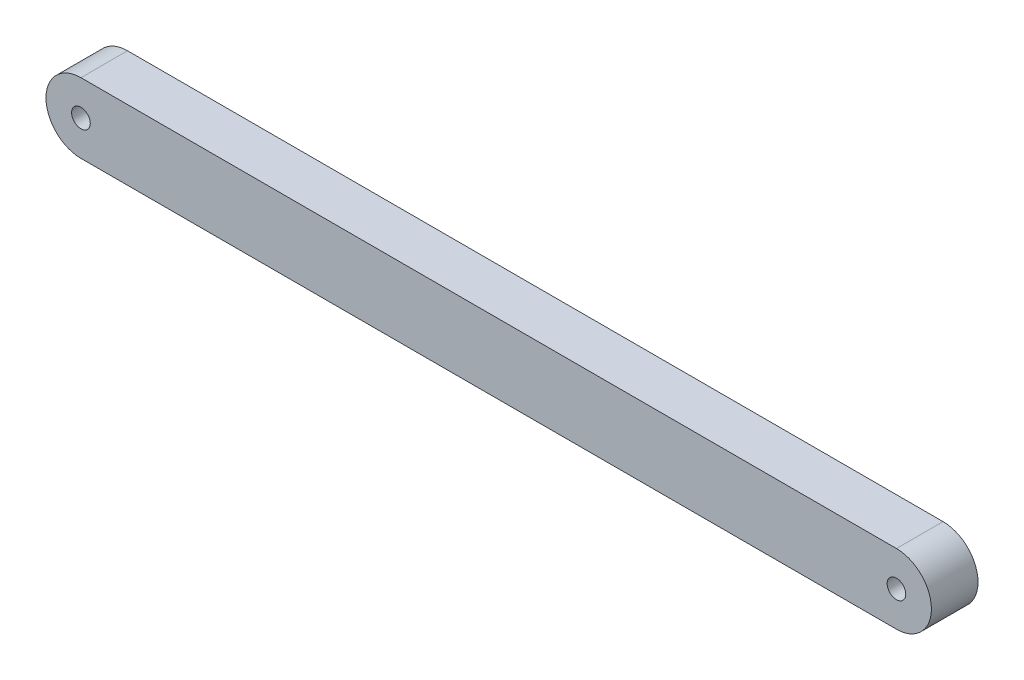
SolidWorks part; units mm, degrees
ref_plane "前视基准面" through (0, 0, 0) normal (0, 0, 1) x (1, 0, 0)
ref_plane "上视基准面" through (0, 0, 0) normal (0, 1, 0) x (1, 0, 0)
ref_plane "右视基准面" through (0, 0, 0) normal (1, 0, 0) x (0, 0, -1)
other "Configuration Table"
sketch "草图1" plane through (0, 0, 0) normal (0, 0, 1) x (1, 0, 0)
  line L0 (0, 0) -> (350, 0) construction
  line L1 (0, -15) -> (350, -15)
  line L2 (0, 15) -> (350, 15)
  arc A0 (0, 15) -> (0, -15) centre (0, 0) ccw
  arc A1 (350, -15) -> (350, 15) centre (350, 0) ccw
  point P4 (348.8935, 0)
extrude "凸台-拉伸1" add sketch "草图1" along normal blind 20
sketch "草图2" plane through (0, 0, 0) normal (0, 0, 1) x (1, 0, 0)
  circle A0 centre (0, 0) radius 4
  circle A1 centre (350, 0) radius 4
extrude "切除-拉伸1" cut sketch "草图2" along normal blind 20
